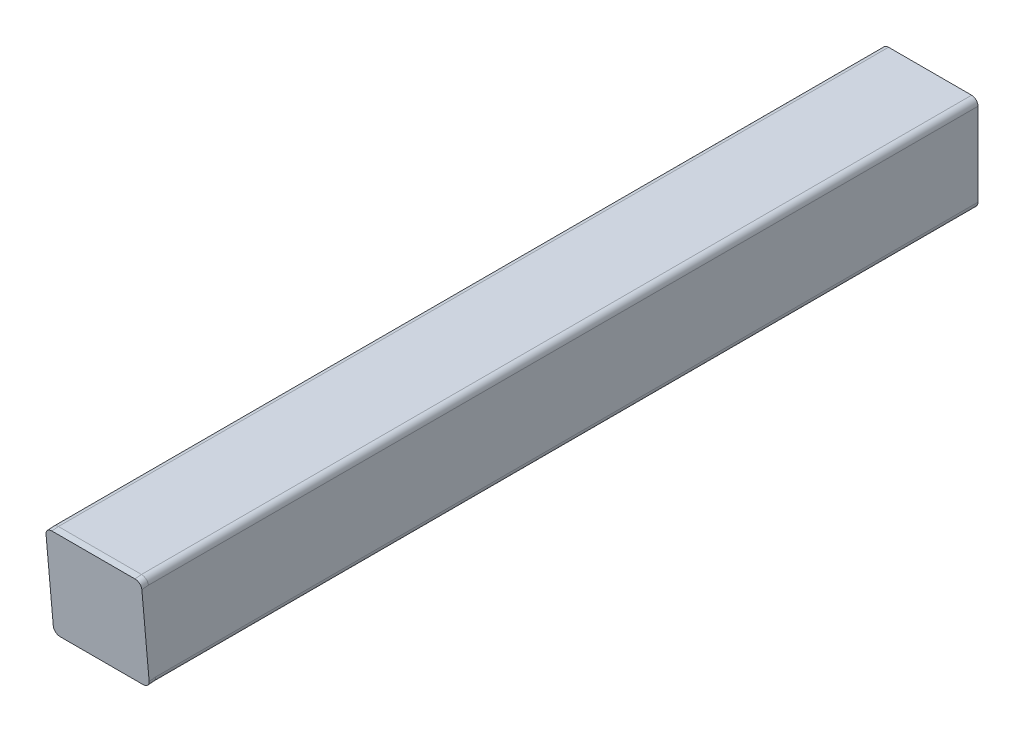
SolidWorks part; units mm, degrees
material "ASTM A500 Grade B Steel"
ref_plane "Front Plane" through (0, 0, 0) normal (0, 0, 1) x (1, 0, 0)
ref_plane "Top Plane" through (0, 0, 0) normal (0, 1, 0) x (1, 0, 0)
ref_plane "Right Plane" through (0, 0, 0) normal (1, 0, 0) x (0, 0, -1)
sketch "Sketch1" plane through (0, 0, 0) normal (0, 0, 1) x (1, 0, 0)
  line L0 (5.3086, -2.7686) -> (32.7914, -2.7686)
  line L1 (2.54, 0) -> (35.56, 0)
  line L2 (0, -2.54) -> (0, -35.56)
  line L3 (2.54, -38.1) -> (35.56, -38.1)
  line L4 (38.1, -2.54) -> (38.1, -35.56)
  line L5 (35.3314, -5.3086) -> (35.3314, -32.7914)
  line L6 (5.3086, -35.3314) -> (32.7914, -35.3314)
  line L7 (2.7686, -5.3086) -> (2.7686, -32.7914)
  line L8 (0, 0) -> (0, -38.1) construction
  line L9 (0, -38.1) -> (38.1, -38.1) construction
  line L10 (38.1, 0) -> (38.1, -38.1) construction
  line L11 (2.7686, -2.7686) -> (2.7686, -35.3314) construction
  line L12 (2.7686, -35.3314) -> (35.3314, -35.3314) construction
  line L13 (35.3314, -2.7686) -> (35.3314, -35.3314) construction
  line L14 (2.7686, -2.7686) -> (35.3314, -2.7686) construction
  line L15 (0, 0) -> (38.1, 0) construction
  arc A0 (0, -35.56) -> (2.54, -38.1) centre (2.54, -35.56) ccw
  arc A1 (38.1, -35.56) -> (35.56, -38.1) centre (35.56, -35.56) cw
  arc A2 (2.7686, -32.7914) -> (5.3086, -35.3314) centre (5.3086, -32.7914) ccw
  arc A3 (32.7914, -35.3314) -> (35.3314, -32.7914) centre (32.7914, -32.7914) ccw
  arc A4 (35.3314, -5.3086) -> (32.7914, -2.7686) centre (32.7914, -5.3086) ccw
  arc A5 (38.1, -2.54) -> (35.56, 0) centre (35.56, -2.54) ccw
  arc A6 (0, -2.54) -> (2.54, 0) centre (2.54, -2.54) cw
  arc A7 (5.3086, -2.7686) -> (2.7686, -5.3086) centre (5.3086, -5.3086) ccw
  point P12 (0, -38.1)
  dimension "D4" = 2.54
  dimension "D3" = 2.7686
extrude "Boss-Extrude1" add sketch "Sketch1" along normal blind 330
sketch "Sketch2" plane through (38.1, 0, 0) normal (1, 0, 0) x (0, 0, -1)
  line L0 (-330, 0) -> (-326.6667, -38.1)
  line L1 (-330, -38.1) -> (0, -38.1) construction
  line L5 (-330, 0) -> (-330, -38.1)
  line L6 (-326.6667, -38.1) -> (-330, -38.1)
  dimension "D1" = 5
extrude "Cut-Extrude1" cut sketch "Sketch2" against normal through all
sketch "Sketch3" plane through (0, -28.6519, 327.4933) normal (0, -0.0872, 0.9962) x (1, 0, 0)
  line L4 (2.54, -9.4841) -> (35.56, -9.4841)
  line L5 (38.1, -6.9344) -> (38.1, 26.2117)
  line L6 (35.56, 28.7614) -> (2.54, 28.7614)
  line L7 (0, 26.2117) -> (0, -6.9344)
  line L8 (2.54, -9.4841) -> (35.56, -9.4841)
  line L9 (38.1, -6.9344) -> (38.1, 26.2117)
  line L10 (35.56, 28.7614) -> (2.54, 28.7614)
  line L11 (0, 26.2117) -> (0, -6.9344)
  ellipse E4 centre (35.56, -6.9344) end of major axis (35.56, -9.4841) minor radius 2.54 (35.56, -9.4841) -> (38.1, -6.9344) ccw
  ellipse E5 centre (35.56, 26.2117) end of major axis (35.56, 23.662) minor radius 2.54 (38.1, 26.2117) -> (35.56, 28.7614) ccw
  ellipse E6 centre (2.54, 26.2117) end of major axis (2.54, 23.662) minor radius 2.54 (2.54, 28.7614) -> (0, 26.2117) ccw
  ellipse E7 centre (2.54, -6.9344) end of major axis (2.54, -9.4841) minor radius 2.54 (0, -6.9344) -> (2.54, -9.4841) ccw
  ellipse E8 centre (35.56, -6.9344) end of major axis (35.56, -9.4841) minor radius 2.54 (35.56, -9.4841) -> (38.1, -6.9344) ccw
  ellipse E9 centre (35.56, 26.2117) end of major axis (35.56, 23.662) minor radius 2.54 (38.1, 26.2117) -> (35.56, 28.7614) ccw
  ellipse E10 centre (2.54, 26.2117) end of major axis (2.54, 23.662) minor radius 2.54 (2.54, 28.7614) -> (0, 26.2117) ccw
  ellipse E11 centre (2.54, -6.9344) end of major axis (2.54, -9.4841) minor radius 2.54 (0, -6.9344) -> (2.54, -9.4841) ccw
  dimension "D1" = 0
extrude "Boss-Extrude2" add sketch "Sketch3" along normal up to surface (2.6153 mm away)
